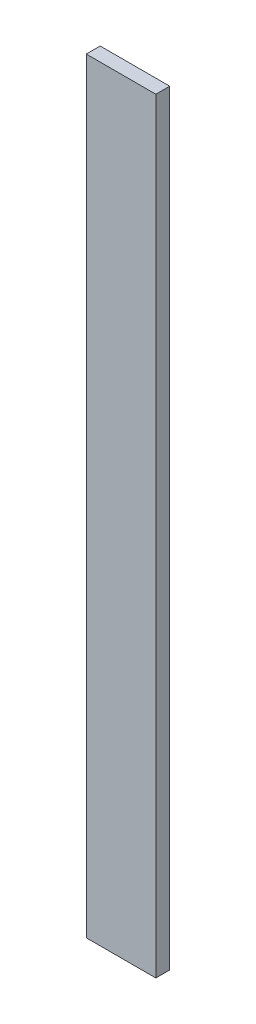
SolidWorks part; units mm, degrees
ref_plane "前视基准面" through (0, 0, 0) normal (0, 0, 1) x (1, 0, 0)
ref_plane "上视基准面" through (0, 0, 0) normal (0, 1, 0) x (1, 0, 0)
ref_plane "右视基准面" through (0, 0, 0) normal (1, 0, 0) x (0, 0, -1)
other "Configuration Table"
sketch "草图1" plane through (0, 0, 0) normal (0, 0, 1) x (1, 0, 0)
  line L1 (-7.5, -82.5) -> (7.5, -82.5)
  line L2 (-7.5, -82.5) -> (-7.5, 82.5)
  line L3 (-7.5, 82.5) -> (7.5, 82.5)
  line L4 (7.5, -82.5) -> (7.5, 82.5)
  line L5 (-7.5, -82.5) -> (7.5, 82.5) construction
  line L6 (-7.5, 82.5) -> (7.5, -82.5) construction
  point P0 (0, 0)
  dimension "D1" = 165
  dimension "D2" = 15
extrude "凸台-拉伸1" add sketch "草图1" along normal blind 3
